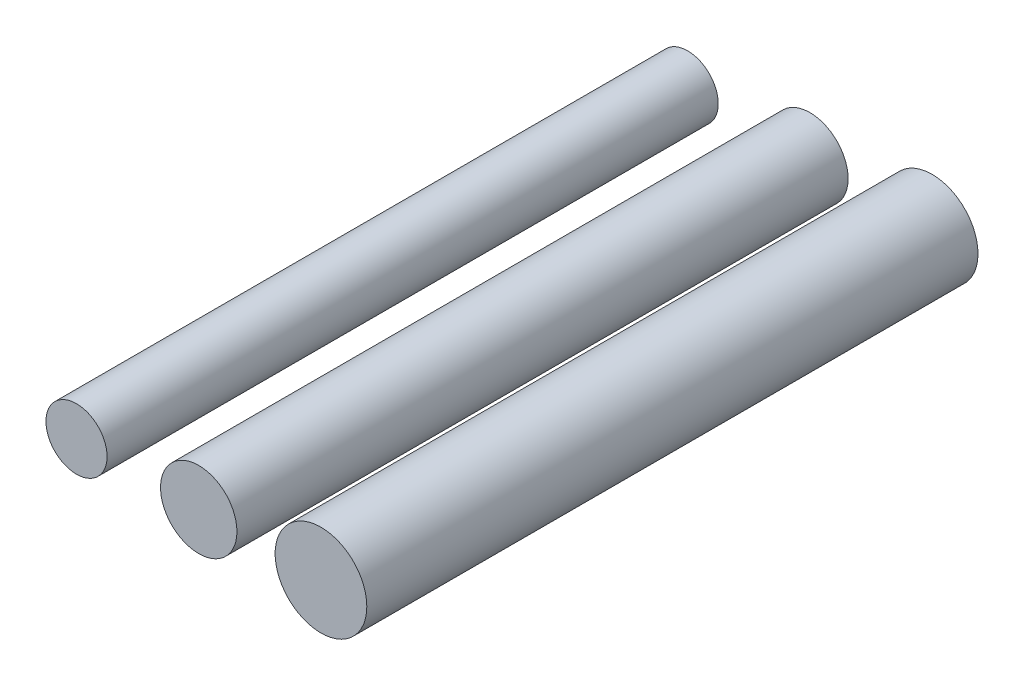
SolidWorks part; units mm, degrees
ref_plane "Front Plane" through (0, 0, 0) normal (0, 0, 1) x (1, 0, 0)
ref_plane "Top Plane" through (0, 0, 0) normal (0, 1, 0) x (1, 0, 0)
ref_plane "Right Plane" through (0, 0, 0) normal (1, 0, 0) x (0, 0, -1)
sketch "Sketch1" plane through (0, 0, 0) normal (0, 0, 1) x (1, 0, 0)
  circle A0 centre (0, 0) radius 1.27
  circle A1 centre (5.08, 0) radius 1.5875
  circle A2 centre (10.16, 0) radius 1.905
  point P7 (0, 0)
  point P8 (0, 0)
  point P10 (9.822, 0.014)
  dimension "D1" = 3.81
  dimension "D2" = 3.175
  dimension "D3" = 2.54
  dimension "D4" = 5.08
  dimension "D5" = 5.08
extrude "Boss-Extrude1" add sketch "Sketch1" along normal blind 25.4
